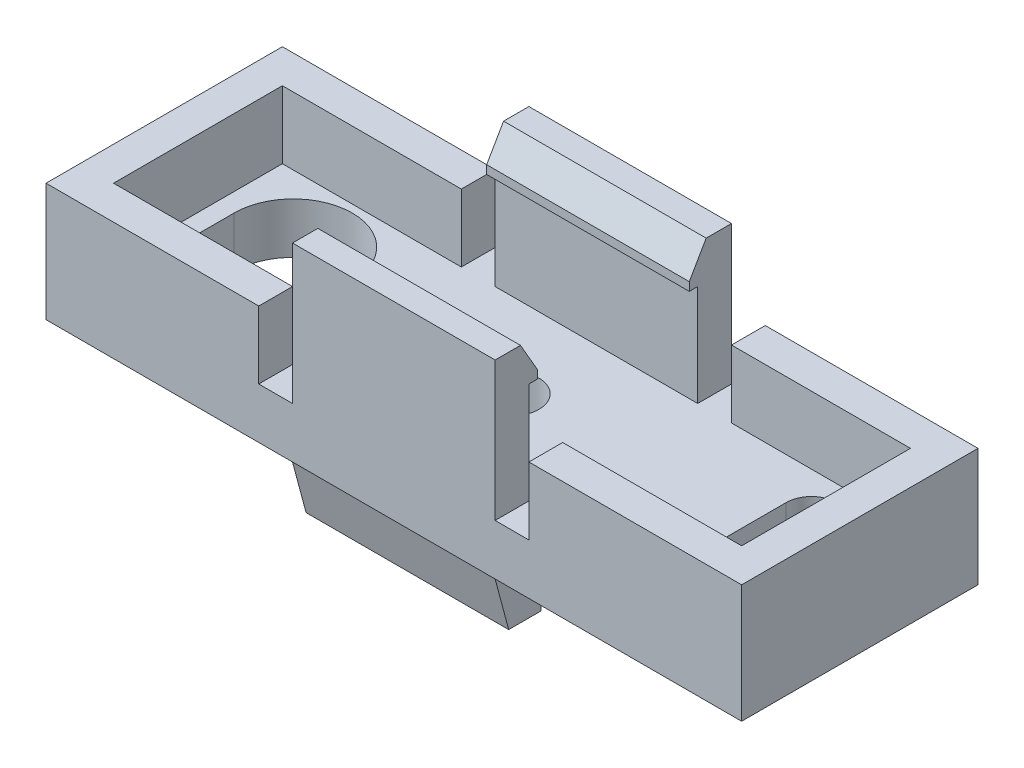
SolidWorks part; units mm, degrees
ref_plane "Front Plane" through (0, 0, 0) normal (0, 0, 1) x (1, 0, 0)
ref_plane "Top Plane" through (0, 0, 0) normal (0, 1, 0) x (1, 0, 0)
ref_plane "Right Plane" through (0, 0, 0) normal (1, 0, 0) x (0, 0, -1)
sketch "Sketch1" plane through (0, 0, 0) normal (0, 1, 0) x (1, 0, 0)
  line L0 (-9.3, -2.5) -> (9.3, 2.5) construction
  line L1 (-10.3, 3.5) -> (10.3, 3.5)
  line L2 (-10.3, 3.5) -> (-10.3, -3.5)
  line L3 (-10.3, -3.5) -> (10.3, -3.5)
  line L4 (10.3, 3.5) -> (10.3, -3.5)
  line L5 (-9.3, 2.5) -> (9.3, 2.5) construction
  line L6 (-9.3, 2.5) -> (-9.3, -2.5) construction
  line L7 (-9.3, -2.5) -> (9.3, -2.5) construction
  line L8 (9.3, 2.5) -> (9.3, -2.5) construction
  dimension "D1" = 5
  dimension "D2" = 18.6
  dimension "D3" = 1
  dimension "D4" = 1
  dimension "D5" = 1
  dimension "D6" = 1
extrude "Boss-Extrude1" add sketch "Sketch1" along normal blind 1.5
sketch "Sketch2" plane through (0, 1.5, 0) normal (0, 1, 0) x (1, 0, 0)
  line L1 (-10.3, -3.5) -> (10.3, -3.5)
  line L2 (-10.3, -3.5) -> (-10.3, 3.5)
  line L3 (-10.3, 3.5) -> (10.3, 3.5)
  line L4 (10.3, -3.5) -> (10.3, 3.5)
  line L5 (-9.3, 2.5) -> (9.3, 2.5)
  line L6 (-9.3, 2.5) -> (-9.3, -2.5)
  line L7 (-9.3, -2.5) -> (9.3, -2.5)
  line L8 (9.3, 2.5) -> (9.3, -2.5)
extrude "Boss-Extrude2" add sketch "Sketch2" along normal blind 2
sketch "Sketch3" plane through (0, 0, 3.5) normal (0, 0, 1) x (1, 0, 0)
  line L0 (-10.3, 3.5) -> (10.3, 3.5) construction
  line L1 (3, 3.5) -> (4, 3.5)
  line L2 (3, 3.5) -> (3, 1.5)
  line L3 (3, 1.5) -> (4, 1.5)
  line L4 (4, 3.5) -> (4, 1.5)
  line L5 (-3, 1.5) -> (3, 1.5) construction
  line L6 (-3, 3.5) -> (-4, 3.5)
  line L7 (-3, 3.5) -> (-3, 1.5)
  line L8 (-3, 1.5) -> (-4, 1.5)
  line L9 (-4, 3.5) -> (-4, 1.5)
  line L10 (0, 1.5) -> (0, 0) construction
  line L11 (-9.3, 1.5) -> (9.3, 1.5) construction
  dimension "D1" = 1
  dimension "D2" = 6
extrude "Cut-Extrude1" cut sketch "Sketch3" against normal through all
sketch "Sketch4" plane through (-3, 0, 0) normal (-1, 0, 0) x (0, 0, 1)
  line L0 (-2.5, 4.5) -> (-2.25, 4.5)
  line L2 (-2.25, 4.5) -> (-2.25, 4.75)
  line L3 (-2.25, 4.75) -> (-2.75, 5.616)
  line L4 (-2.75, 5.616) -> (-3.5, 5.616)
  line L5 (-3.5, 5.616) -> (-3.5, 3.8761)
  line L6 (-2.5, 3.5) -> (-2.5, 1.5) construction
  line L7 (-3.5, 3.5) -> (-3.5, 0) construction
  line L8 (-2.5, 1.5) -> (2.5, 1.5) construction
  line L9 (-2.5, 3.5) -> (-3.5, 3.5)
  line L10 (-2.5, 3.5) -> (-2.5, 4.5)
  line L12 (-3.5, 3.5) -> (-3.5, 3.8761)
  dimension "D1" = 0.25
  dimension "D2" = 30
  dimension "D3" = 0.25
  dimension "D4" = 0.25
  dimension "D5" = 3
extrude "Boss-Extrude3" add sketch "Sketch4" against normal up to surface (6 mm away) up to face at (3, 2.5, -3)
mirror "Mirror1" about plane through (0, 0, 0) normal (0, 0, 1) of "Boss-Extrude3"
sketch "Sketch6" plane through (0, 1.5, 0) normal (0, 1, 0) x (1, 0, 0)
  line L0 (7.6, 1.27) -> (7.6, -1.27) construction
  line L1 (8.35, 1.27) -> (8.35, -1.27)
  line L2 (6.85, 1.27) -> (6.85, -1.27)
  line L3 (-7, 0.52) -> (-7, -0.52) construction
  line L4 (-5.25, 0.52) -> (-5.25, -0.52)
  line L5 (-8.75, 0.52) -> (-8.75, -0.52)
  line L6 (7.6, 2.02) -> (-1.4504, 0.7893) construction
  arc A0 (8.35, 1.27) -> (6.85, 1.27) centre (7.6, 1.27) ccw
  arc A1 (6.85, -1.27) -> (8.35, -1.27) centre (7.6, -1.27) ccw
  arc A2 (-5.25, 0.52) -> (-8.75, 0.52) centre (-7, 0.52) ccw
  arc A3 (-8.75, -0.52) -> (-5.25, -0.52) centre (-7, -0.52) ccw
  point P2 (7.6, 0)
  point P7 (-7, 0)
  dimension "D1" = 1.5
  dimension "D2" = 2.54
  dimension "D3" = 3.5
  dimension "D4" = 1.04
  dimension "D5" = 7.6
  dimension "D6" = 7
extrude "Cut-Extrude3" cut sketch "Sketch6" against normal through all
sketch "Sketch8" plane through (0, 0, 0) normal (1, 0, 0) x (0, 0, -1)
  line L0 (-3.5, 0) -> (-3.0981, -1.5)
  line L1 (-3.0981, -1.5) -> (-2.145, -1.5)
  line L2 (-0.395, -1.5) -> (0.87, -1.5)
  line L3 (0.87, -1.5) -> (0.87, -1)
  line L4 (3.2321, -1) -> (1.67, -1)
  line L5 (3.2321, -1) -> (3.5, 0)
  line L6 (3.5, 0) -> (-3.5, 0)
  arc A0 (-2.145, -1.5) -> (-0.395, -1.5) centre (-1.27, -1.5) cw
  arc A1 (0.87, -1) -> (1.67, -1) centre (1.27, -1) cw
  dimension "D3" = 0.4
  dimension "D5" = 0.875
  dimension "D1" = 1.27
  dimension "D2" = 1.5
  dimension "D4" = 1.27
  dimension "D6" = 75
  dimension "D7" = 75
  dimension "D8" = 1
extrude "Boss-Extrude4" add sketch "Sketch8" along normal mid plane 6
sketch "Sketch5" plane through (0, 1.5, 0) normal (0, 1, 0) x (1, 0, 0)
  circle A0 centre (0, 0) radius 0.8
  circle A1 centre (8.95, -2) radius 0.4
  dimension "D1" = 1.6
  dimension "D2" = 0.8
  dimension "D3" = 8.95
  dimension "D4" = 2
extrude "Cut-Extrude2" cut sketch "Sketch5" against normal through all
